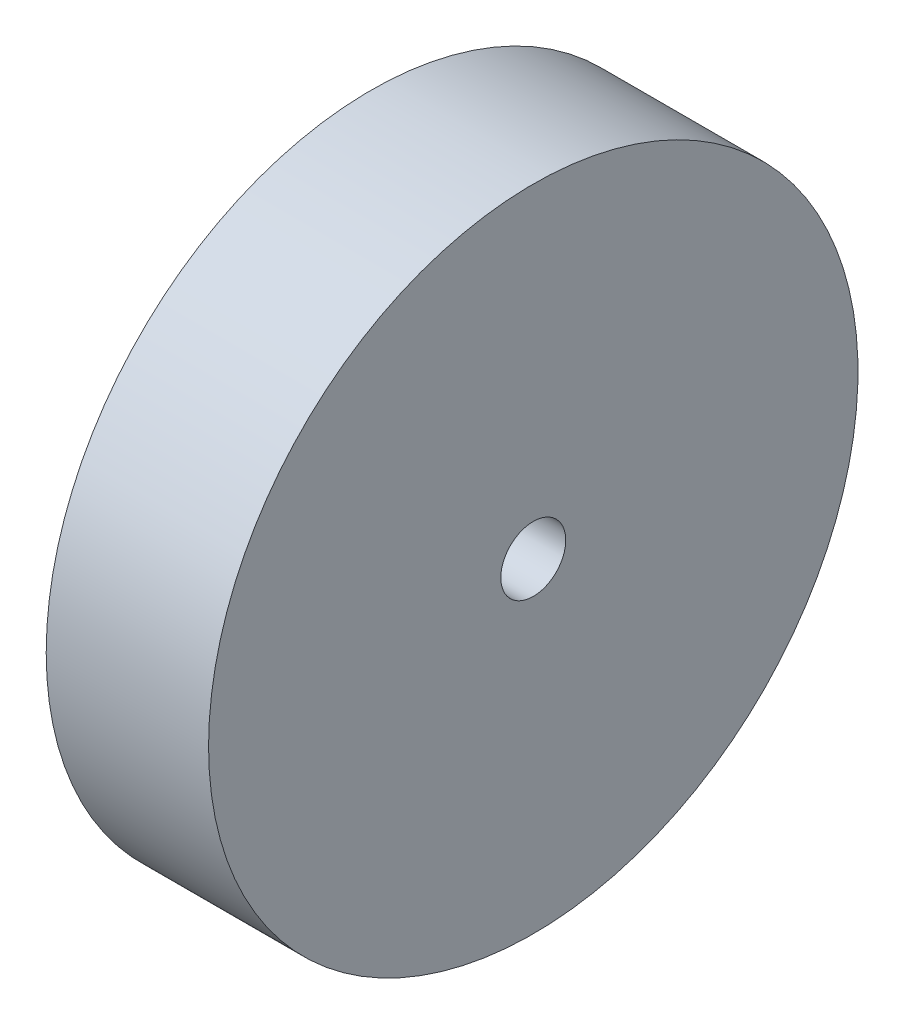
SolidWorks part; units mm, degrees
ref_plane "Front Plane" through (0, 0, 0) normal (0, 0, 1) x (1, 0, 0)
ref_plane "Top Plane" through (0, 0, 0) normal (0, 1, 0) x (1, 0, 0)
ref_plane "Right Plane" through (0, 0, 0) normal (1, 0, 0) x (0, 0, -1)
sketch "Sketch1" plane through (0, 0, 0) normal (0, 0, 1) x (1, 0, 0)
  line L0 (0, 0) -> (5.1881, 0) construction
  line L1 (-2.5, 1) -> (2.5, 1)
  line L2 (-2.5, 1) -> (-2.5, 10)
  line L3 (-2.5, 10) -> (2.5, 10)
  line L4 (2.5, 1) -> (2.5, 10)
  dimension "D1" = 10
  dimension "D2" = 5
  dimension "D3" = 1
  dimension "D4" = 2.5
revolve "Revolve1" add sketch "Sketch1" angle 360 about L0
